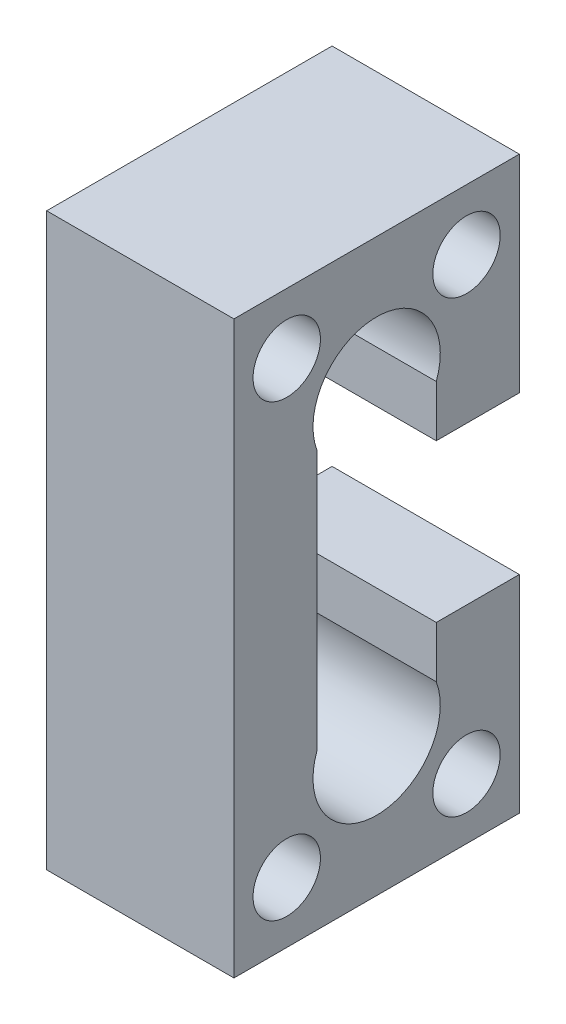
SolidWorks part; units mm, degrees
material "AISI 4140 Steel "
ref_plane "Front Plane" through (0, 0, 0) normal (0, 0, 1) x (1, 0, 0)
ref_plane "Top Plane" through (0, 0, 0) normal (0, 1, 0) x (1, 0, 0)
ref_plane "Right Plane" through (0, 0, 0) normal (1, 0, 0) x (0, 0, -1)
sketch "Sketch1" plane through (0, 0, 0) normal (0, 0, 1) x (1, 0, 0)
  line L0 (-12.5, 38.1) -> (12.5, -38.1) construction
  line L1 (-12.5, -38.1) -> (12.5, -38.1)
  line L2 (-12.5, -38.1) -> (-12.5, 38.1)
  line L3 (-12.5, 38.1) -> (12.5, 38.1)
  line L4 (12.5, -38.1) -> (12.5, 38.1)
  dimension "D1" = 76.2
  dimension "D2" = 25
extrude "Extrude1" add sketch "Sketch1" against normal mid plane 38.1
hole_wizard "M16 Clearance Hole1" positions "Sketch5" profile "Sketch4" hole size "M16" standard "Peddi DIN" end condition through all
sketch "Sketch5" plane through (-12.5, 0, 0) normal (-1, 0, 0) x (0, 0, 1)
  line L0 (0, -20.32) -> (0, 20.32) construction
  line L2 (0, 0) -> (-19.05, 0) construction
  line L3 (-19.05, 38.1) -> (-19.05, -38.1) construction
  line L4 (0, 20.32) -> (0, 38.1) construction
  line L5 (-19.05, 38.1) -> (19.05, 38.1) construction
  point P0 (0, -20.32)
  point P1 (0, 20.32)
  dimension "D1" = 40.64
sketch "Sketch4" plane through (-12.5, -20.32, 0) normal (0, 1, 0) x (0, 0, 1)
  line L0 (0, 0) -> (0, 25)
  line L1 (0, 25) -> (8.4963, 25)
  line L2 (8.4963, 25) -> (8.4963, 0)
  line L5 (8.4963, 0) -> (0, 0)
  line L11 (0, -6.35) -> (0, 107.95) construction
  dimension "Thru Hole Dia." = 16.9926
  dimension "Thru Hole Depth" = 25
sketch "Sketch2" plane through (12.5, 0, 0) normal (1, 0, 0) x (0, 0, -1)
  line L0 (0, 38.1) -> (0, 20) construction
  line L1 (19.05, 10.5) -> (7.9629, 10.5)
  line L2 (19.05, 38.1) -> (19.05, -38.1) construction
  line L3 (7.9629, 10.5) -> (7.9629, 20)
  line L4 (7.9629, 20) -> (-7.9629, 20)
  line L5 (-7.9629, 20) -> (-7.9629, -20)
  line L6 (-7.9629, -20) -> (7.9629, -20)
  line L7 (7.9629, -20) -> (7.9629, -10.5)
  line L8 (7.9629, -10.5) -> (19.05, -10.5)
  line L9 (19.05, -10.5) -> (19.05, 10.5)
  line L10 (-7.9629, 0) -> (19.05, 0) construction
  line L11 (19.05, 38.1) -> (-19.05, 38.1) construction
  dimension "D1" = 21
  dimension "D2" = 40
  dimension "D3" = 15.9258
extrude "Extrude3" cut sketch "Sketch2" against normal through all
hole_wizard "M8 Clearance Hole1" positions "Sketch12" profile "Sketch11" hole size "M8" standard "Peddi DIN" end condition through all
sketch "Sketch12" plane through (12.5, 0, 0) normal (1, 0, 0) x (0, 0, -1)
  line L0 (12, 30) -> (12, -30) construction
  line L1 (12, -30) -> (-12, -30) construction
  line L2 (-12, -30) -> (12, 30) construction
  line L3 (12, 30) -> (-12, 30) construction
  point P0 (-12, 30)
  point P2 (12, 30)
  point P4 (12, -30)
  point P6 (-12, -30)
  dimension "D1" = 60
  dimension "D2" = 24
sketch "Sketch11" plane through (12.5, 30, 12) normal (0, 1, 0) x (0, 0, -1)
  line L0 (0, 0) -> (0, 25)
  line L1 (0, 25) -> (4.5, 25)
  line L2 (4.5, 25) -> (4.5, 0)
  line L5 (4.5, 0) -> (0, 0)
  line L11 (0, -6.35) -> (0, 107.95) construction
  dimension "Thru Hole Dia." = 9
  dimension "Thru Hole Depth" = 25
other "Freeze***"
